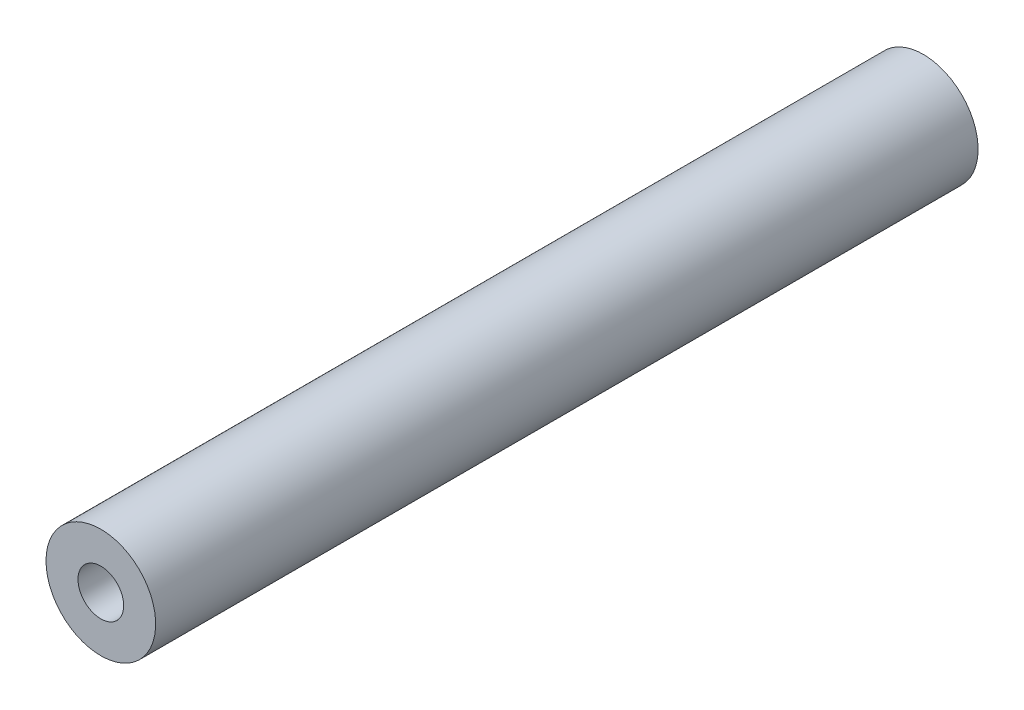
SolidWorks part; units mm, degrees
ref_plane "Plano frontal" through (0, 0, 0) normal (0, 0, 1) x (1, 0, 0)
ref_plane "Plano superior" through (0, 0, 0) normal (0, 1, 0) x (1, 0, 0)
ref_plane "Plano direito" through (0, 0, 0) normal (1, 0, 0) x (0, 0, -1)
sketch "Esboço1" plane through (0, 0, 0) normal (0, 0, 1) x (1, 0, 0)
  circle A0 centre (0, 0) radius 3
  dimension "D1" = 6
extrude "Ressalto-extrusão1" add sketch "Esboço1" along normal blind 45
hole_wizard "Broca de rosquear para tarraxa de M31" positions "3DSketch1" profile "Esboço3" hole size "M3" standard "ISO"
sketch3d "3DSketch1"
  line L0 (0, 0, 45) -> (0, 0, 0) construction
  point P0 (0, 0, 45)
sketch "Esboço3" plane through (0, 0, 45) normal (1, 0, 0) x (0, -1, 0)
  line L0 (0, 0) -> (0, 8.7511)
  line L1 (0, 8.7511) -> (1.25, 8)
  line L2 (1.25, 8) -> (1.25, 0)
  line L5 (1.25, 0) -> (0, 0)
  line L10 (0, 8.7511) -> (-1.25, 8) construction
  line L11 (0, -6.35) -> (0, 107.95) construction
  dimension "Hole Dia." = 2.5
  dimension "Hole Depth" = 8
  dimension "Drill Angle" = 118
hole_wizard "Broca de rosquear para tarraxa de M32" positions "3DSketch10" profile "Esboço15" hole size "M3" standard "ISO"
sketch3d "3DSketch10"
  point P0 (0, 0, 0)
  point P3 (0, 0, 0)
  point P5 (0, 0, 0)
  point P7 (0, 0, 0)
  point P9 (0, 0, 0)
sketch "Esboço15" plane through (0, 0, 0) normal (1, 0, 0) x (0, 1, 0)
  line L0 (0, 0) -> (0, 8.7511)
  line L1 (0, 8.7511) -> (1.25, 8)
  line L2 (1.25, 8) -> (1.25, 0)
  line L5 (1.25, 0) -> (0, 0)
  line L10 (0, 8.7511) -> (-1.25, 8) construction
  line L11 (0, -6.35) -> (0, 107.95) construction
  dimension "Hole Dia." = 2.5
  dimension "Hole Depth" = 8
  dimension "Drill Angle" = 118
